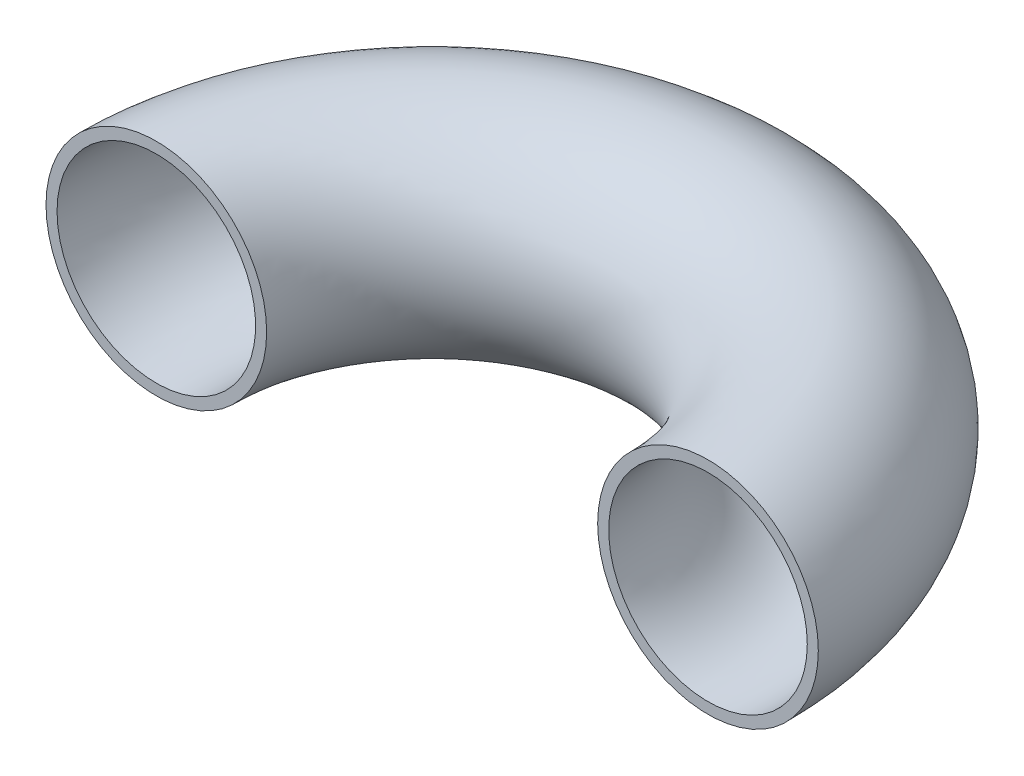
SolidWorks part; units mm, degrees
material "Plain Carbon Steel"
ref_plane "Front Plane" through (0, 0, 0) normal (0, 0, 1) x (1, 0, 0)
ref_plane "Top Plane" through (0, 0, 0) normal (0, 1, 0) x (1, 0, 0)
ref_plane "Right Plane" through (0, 0, 0) normal (1, 0, 0) x (0, 0, -1)
sketch "Sketch1" plane through (0, 0, 0) normal (0, 0, 1) x (1, 0, 0)
  circle A0 centre (0, 0) radius 5
  dimension "D1" = 10
sketch "Sketch2" plane through (0, 0, 0) normal (0, 1, 0) x (1, 0, 0)
  arc A0 (0, 0) -> (25, 0) centre (12.5, 0) cw
  point P3 (0, 0)
  point P5 (0, 0)
  dimension "D1" = 12.5
sweep "Sweep1" add profiles "Sketch1" path "Sketch2"
shell "Shell1" thickness 0.5
